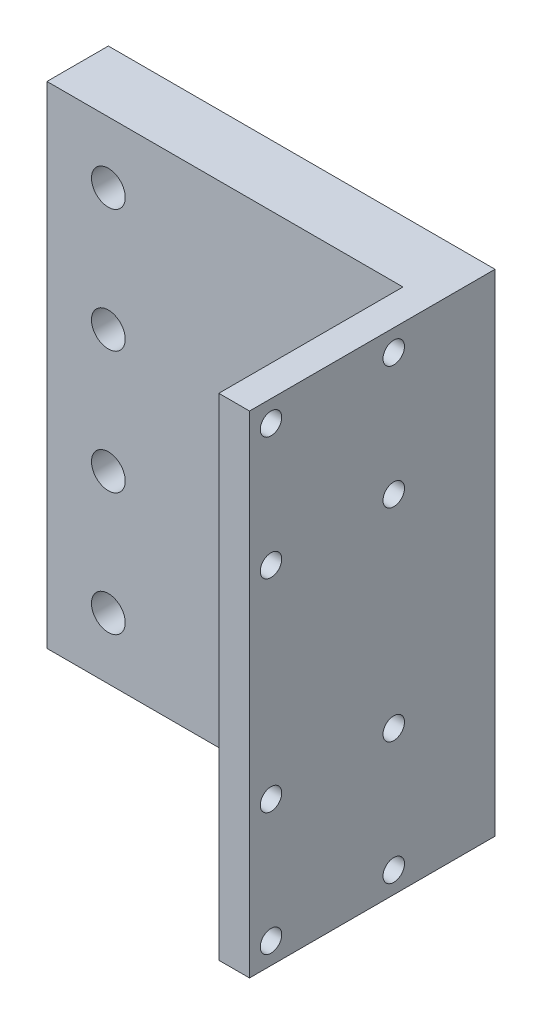
SolidWorks part; units mm, degrees
ref_plane "Plan de face" through (0, 0, 0) normal (0, 0, 1) x (1, 0, 0)
ref_plane "Plan de dessus" through (0, 0, 0) normal (0, 1, 0) x (1, 0, 0)
ref_plane "Plan de droite" through (0, 0, 0) normal (1, 0, 0) x (0, 0, -1)
sketch "Esquisse1" plane through (0, 0, 0) normal (0, 0, 1) x (1, 0, 0)
  line L1 (-33.3969, 24.3516) -> (29.6031, 24.3516)
  line L2 (-33.3969, 24.3516) -> (-33.3969, -55.6484)
  line L3 (-33.3969, -55.6484) -> (29.6031, -55.6484)
  line L4 (29.6031, 24.3516) -> (29.6031, -55.6484)
  circle A0 centre (-23.3969, 14.3516) radius 2.75
  circle A1 centre (-23.3969, -5.6484) radius 2.75
  circle A2 centre (-23.3969, -25.6484) radius 2.75
  circle A3 centre (-23.3969, -45.6484) radius 2.75
  dimension "D3" = 5.5
  dimension "D1" = 80
  dimension "D2" = 63
  dimension "D4" = 10
  dimension "D5" = 10
  dimension "D6" = 20
  dimension "D7" = 20
  dimension "D8" = 10
extrude "Boss.-Extru.1" add sketch "Esquisse1" along normal blind 10
sketch "Esquisse2" plane through (0, 0, 10) normal (0, 0, -1) x (-1, 0, 0)
  line L0 (-29.6031, 24.3516) -> (33.3969, 24.3516) construction
  line L1 (-29.6031, -55.6484) -> (-24.6031, -55.6484)
  line L2 (-29.6031, -55.6484) -> (-29.6031, 24.3516)
  line L3 (-29.6031, 24.3516) -> (-24.6031, 24.3516)
  line L4 (-24.6031, -55.6484) -> (-24.6031, 24.3516)
  dimension "D1" = 5
extrude "Boss.-Extru.2" add sketch "Esquisse2" against normal blind 30
sketch "Esquisse3" plane through (29.6031, 0, 0) normal (1, 0, 0) x (0, 0, -1)
  line L0 (-16.5, -52.1484) -> (-36.5, -52.1484) construction
  line L1 (-36.5, -52.1484) -> (-36.5, -32.1484) construction
  line L2 (-36.5, 20.8516) -> (-16.5, 20.8516) construction
  line L3 (-16.5, 20.8516) -> (-16.5, 0.8516) construction
  line L4 (-40, 24.3516) -> (-40, -55.6484) construction
  line L5 (-40, -55.6484) -> (0, -55.6484) construction
  line L6 (-40, 24.3516) -> (0, 24.3516) construction
  circle A0 centre (-36.5, -52.1484) radius 1.75
  circle A1 centre (-36.5, -32.1484) radius 1.75
  circle A2 centre (-16.5, -32.1484) radius 1.75
  circle A3 centre (-16.5, -52.1484) radius 1.75
  circle A4 centre (-36.5, 0.8516) radius 1.75
  circle A5 centre (-36.5, 20.8516) radius 1.75
  circle A6 centre (-16.5, 20.8516) radius 1.75
  circle A7 centre (-16.5, 0.8516) radius 1.75
  dimension "D1" = 3.5
  dimension "D2" = 20
  dimension "D3" = 3.5
  dimension "D4" = 3.5
  dimension "D5" = 3.5
extrude "Enlèv. mat.-Extru.1" cut sketch "Esquisse3" against normal up to next
sketch "Esquisse4" plane through (0, 0, 0) normal (0, 0, -1) x (-1, 0, 0)
  circle A0 centre (23.3969, -45.6484) radius 6
  circle A1 centre (23.3969, -25.6484) radius 6
  circle A2 centre (23.3969, -5.6484) radius 6
  circle A3 centre (23.3969, 14.3516) radius 6
  dimension "D1" = 12
extrude "Enlèv. mat.-Extru.2" cut sketch "Esquisse4" against normal blind 5
